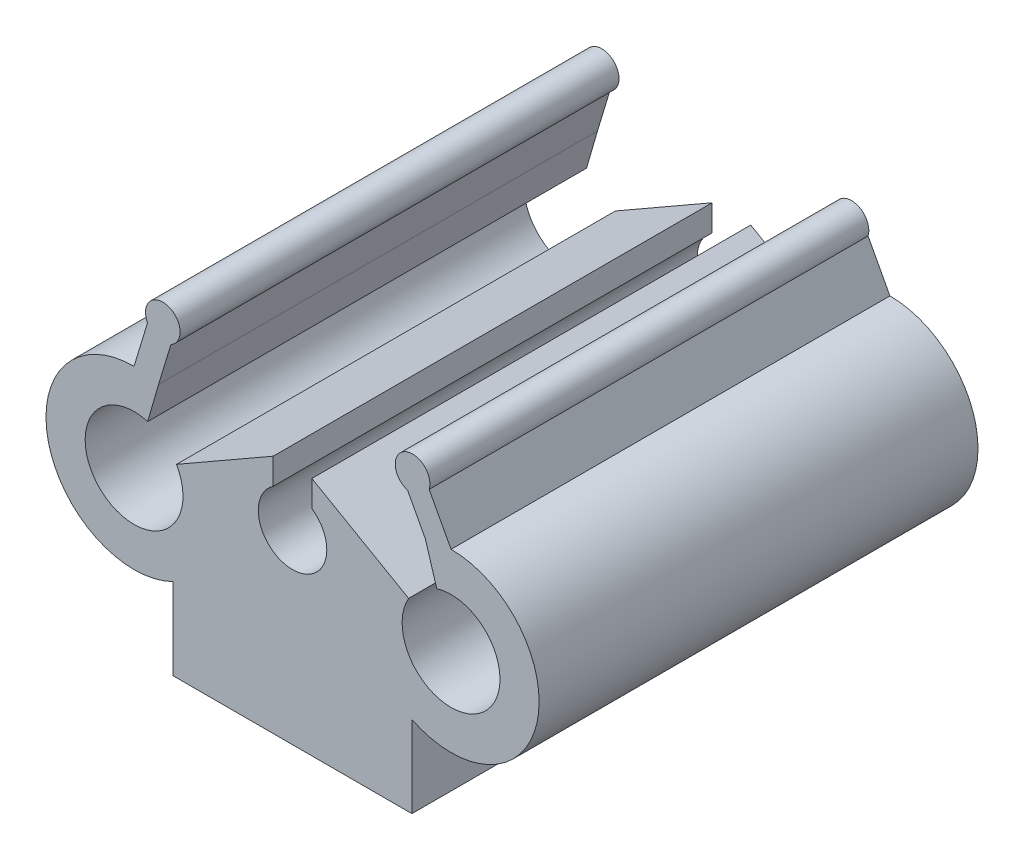
SolidWorks part; units mm, degrees
ref_plane "Ön Düzlem" through (0, 0, 0) normal (0, 0, 1) x (1, 0, 0)
ref_plane "Üst Düzlem" through (0, 0, 0) normal (0, 1, 0) x (1, 0, 0)
ref_plane "Sağ Düzlem" through (0, 0, 0) normal (1, 0, 0) x (0, 0, -1)
sketch "Çizim1" plane through (0, 0, 0) normal (0, 0, 1) x (1, 0, 0)
  line L0 (0, 0) -> (12.2, 0)
  line L1 (12.2, 0) -> (12.2, 4.1689)
  line L3 (0, 4.1689) -> (0, 0)
  line L4 (-2, 12.7) -> (-1.3113, 14.9713)
  line L5 (5.1136, 12.2788) -> (5.1136, 10.9455)
  line L6 (-0.1151, 14.6086) -> (-0.7477, 12.5222)
  line L7 (14.2, 12.7) -> (13.0809, 14.793)
  line L8 (7.0864, 12.2788) -> (7.0864, 10.9455)
  line L9 (11.9786, 14.2036) -> (12.8872, 12.5043)
  line L10 (1.9038, 10.4384) -> (5.1136, 12.2788)
  line L11 (10.2962, 10.4384) -> (7.0864, 12.2788)
  line L12 (10.2962, 10.4384) -> (12.0312, 9.4435)
  line L13 (12.8872, 12.5043) -> (13.4707, 10.5913)
  line L14 (1.9038, 10.4384) -> (0.1688, 9.4435)
  line L15 (-0.7477, 12.5222) -> (-1.3043, 10.6012)
  arc A2 (12.2, 4.1689) -> (14.2, 12.7) centre (14.2, 8.2) ccw
  arc A3 (-2, 12.7) -> (0, 4.1689) centre (-2, 8.2) ccw
  arc A4 (-1.3043, 10.6012) -> (0.1688, 9.4435) centre (-2, 8.2) ccw
  arc A5 (12.0312, 9.4435) -> (13.4707, 10.5913) centre (14.2, 8.2) ccw
  arc A7 (-0.1151, 14.6086) -> (-1.3113, 14.9713) centre (-0.5314, 15.3896) ccw
  arc A8 (13.0809, 14.793) -> (11.9786, 14.2036) centre (12.2343, 15.0509) ccw
  arc A10 (5.1136, 10.9455) -> (7.0864, 10.9455) centre (6.1, 9.5) ccw
  arc A11 (5.1136, 12.2788) -> (4.2001, 11.755) centre (6.1, 9.5) ccw
  arc A12 (7.9999, 11.755) -> (7.0864, 12.2788) centre (6.1, 9.5) ccw
  arc A13 (12.8872, 12.5043) -> (10.2962, 10.4384) centre (14.2, 8.2) ccw
  dimension "D3" = 9
  dimension "D4" = 9
  dimension "D9" = 5
  dimension "D10" = 5
  dimension "D13" = 1.77
  dimension "D16" = 1.77
  dimension "D20" = 3.5
  dimension "D1" = 12.2
  dimension "D5" = 2
  dimension "D6" = 2
  dimension "D7" = 8.2
  dimension "D8" = 8.2
  dimension "D17" = 3.7
  dimension "D18" = 3.7
  dimension "D19" = 9.5
extrude "Yükseklik-Ekstrüzyon1" add sketch "Çizim1" along normal blind 22.43 contours A10 L5 L10 L14 A4 L15 L6 A7 L4 A3 L3 L0 L1 A2 L7 A8 L9 L13 A5 L12 L11 L8
